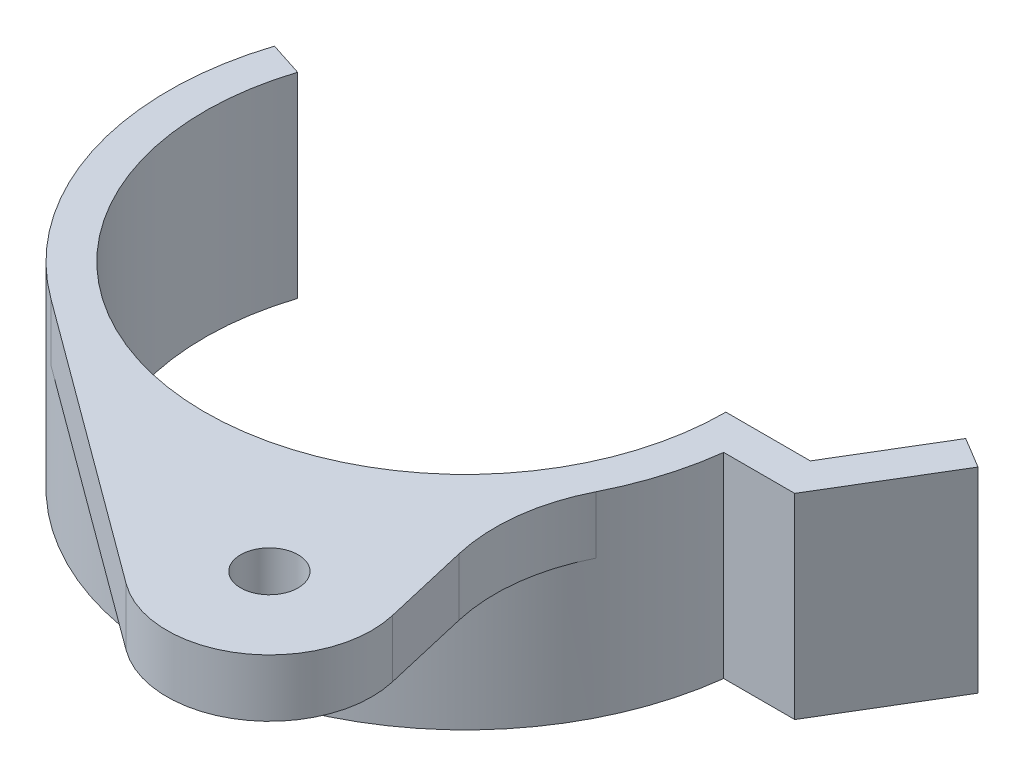
SolidWorks part; units mm, degrees
ref_plane "Front Plane" through (0, 0, 0) normal (0, 0, 1) x (1, 0, 0)
ref_plane "Top Plane" through (0, 0, 0) normal (0, 1, 0) x (1, 0, 0)
ref_plane "Right Plane" through (0, 0, 0) normal (1, 0, 0) x (0, 0, -1)
sketch "Sketch2" plane through (0, 0, 0) normal (0, 1, 0) x (1, 0, 0)
  line L0 (0, 0) -> (47, 0)
  line L1 (47, 0) -> (79.4474, 54.0015)
  line L2 (58.3155, -20) -> (96.5907, 43.7008)
  line L3 (18.7834, -20) -> (58.3155, -20)
  line L4 (-301.9866, 50.7958) -> (-282.9579, 44.6387)
  line L5 (79.4474, 54.0015) -> (96.5907, 43.7008)
  arc A0 (0, 0) -> (-282.9579, 44.6387) centre (-145, 0) cw
  arc A1 (18.7834, -20) -> (-301.9866, 50.7958) centre (-145, 0) cw
  dimension "D2" = 145
  dimension "D1" = 121
  dimension "D3" = 20
extrude "Boss-Extrude1" add sketch "Sketch2" against normal blind 109
sketch "Sketch3" plane through (0, 0, 0) normal (0, 1, 0) x (1, 0, 0)
  line L0 (-242.7641, -132.9179) -> (-84.0682, -249.6424)
  line L1 (5.2275, -190.8319) -> (-15.3788, -102.0948)
  arc A0 (-301.9866, 50.7958) -> (18.7834, -20) centre (-145, 0) ccw construction
  arc A1 (-84.0682, -249.6424) -> (5.2275, -190.8319) centre (-50.2951, -203.7253) ccw
  arc A2 (-242.7641, -132.9179) -> (-15.3788, -102.0948) centre (-145, 0) ccw
  dimension "D1" = 197
  dimension "D2" = 57
extrude "Boss-Extrude2" add sketch "Sketch3" against normal blind 32
fillet "Fillet1" radius 100 1 edges at (-15.3788, -16, 102.0948)
sketch "Sketch4" plane through (0, 0, 0) normal (0, 1, 0) x (1, 0, 0)
  circle A0 centre (-50.2951, -203.7253) radius 16
extrude "Cut-Extrude1" cut sketch "Sketch4" against normal blind 32
